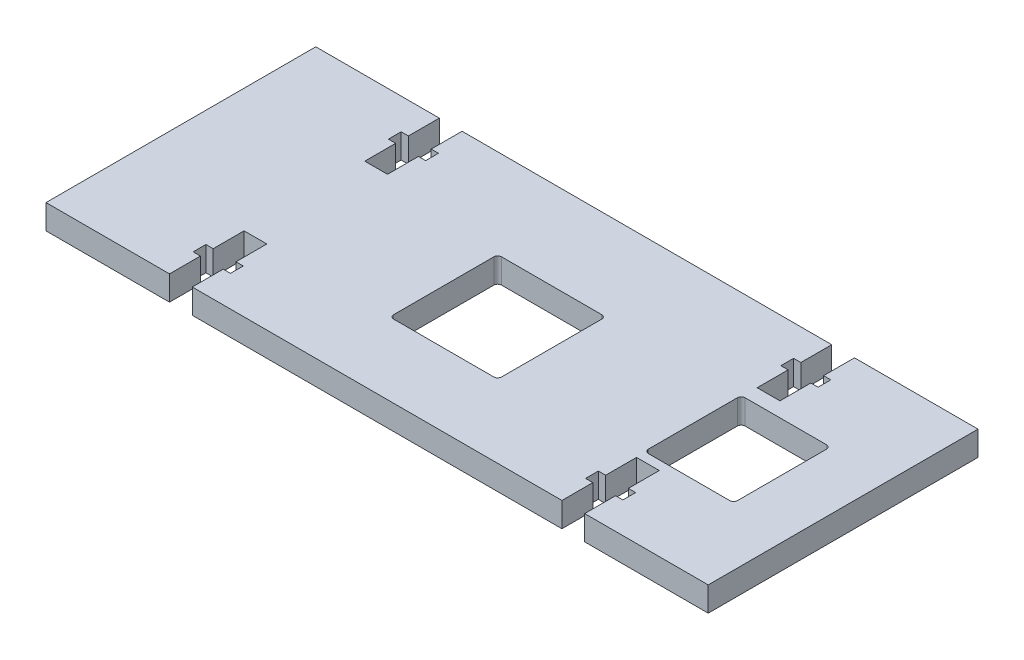
SolidWorks part; units mm, degrees
ref_plane "Front Plane" through (0, 0, 0) normal (0, 0, 1) x (1, 0, 0)
ref_plane "Top Plane" through (0, 0, 0) normal (0, 1, 0) x (1, 0, 0)
ref_plane "Right Plane" through (0, 0, 0) normal (1, 0, 0) x (0, 0, -1)
sketch "Sketch1" plane through (0, 0, 0) normal (0, 1, 0) x (1, 0, 0)
  line L1 (-42.8625, -17.4625) -> (42.8625, -17.4625)
  line L2 (-42.8625, -17.4625) -> (-42.8625, 17.4625)
  line L3 (-42.8625, 17.4625) -> (42.8625, 17.4625)
  line L4 (42.8625, -17.4625) -> (42.8625, 17.4625)
  line L5 (-42.8625, -17.4625) -> (42.8625, 17.4625) construction
  line L6 (-42.8625, 17.4625) -> (42.8625, -17.4625) construction
  point P0 (0, 0)
  dimension "D1" = 85.725
  dimension "D2" = 34.925
extrude "Boss-Extrude1" add sketch "Sketch1" along normal blind 3.175
sketch "Sketch2" plane through (0, 0, 0) normal (0, -1, 0) x (-1, 0, 0)
  line L0 (3.3881, -2.4141) -> (-1.7731, 0.3271) construction
  line L2 (7.7925, 5.9415) -> (-6.1775, 5.9415)
  line L3 (7.7925, 5.9415) -> (7.7925, -8.0285)
  line L4 (7.7925, -8.0285) -> (-6.1775, -8.0285)
  line L5 (-6.1775, 5.9415) -> (-6.1775, -8.0285)
  line L6 (7.7925, 5.9415) -> (-6.1775, -8.0285) construction
  line L7 (7.7925, -8.0285) -> (-6.1775, 5.9415) construction
  line L8 (-23.7675, -6.6175) -> (-35.3075, -6.6175)
  line L12 (-23.7675, 5.9065) -> (-23.7675, -6.6175)
  line L13 (-35.3075, 5.9065) -> (-23.7675, 5.9065)
  line L14 (-35.3075, 5.9065) -> (-35.3075, -6.6175)
  point P4 (0.8075, -1.0435)
  dimension "D1" = 13.97
  dimension "D2" = 13.97
extrude "Cut-Extrude1" cut sketch "Sketch2" against normal through all
fillet "Fillet1" radius 0.508 8 edges at (6.1775, 1.5875, -5.9415) (-7.7925, 1.5875, -5.9415) (6.1775, 1.5875, 8.0285) (-7.7925, 1.5875, 8.0285) (35.3075, 1.5875, -5.9065) (23.7675, 1.5875, -5.9065) (35.3075, 1.5875, 6.6175) (23.7675, 1.5875, 6.6175)
sketch "Sketch3" plane through (0, 0, 0) normal (0, -1, 0) x (1, 0, 0)
  line L0 (-42.8625, 17.4625) -> (42.8625, 17.4625) construction
  line L1 (-26.8732, 17.4625) -> (-23.9268, 17.4625)
  line L2 (-26.8732, 17.4625) -> (-26.8732, 13.462)
  line L3 (-26.8732, 7.8105) -> (-23.9268, 7.8105)
  line L4 (-23.9268, 17.4625) -> (-23.9268, 13.462)
  line L5 (-26.8732, 17.4625) -> (-23.9268, 7.8105) construction
  line L6 (-26.8732, 13.462) -> (-27.813, 13.462)
  line L7 (-22.987, 11.811) -> (-23.9268, 11.811)
  line L8 (-22.987, 11.811) -> (-22.987, 13.462)
  line L9 (-22.987, 13.462) -> (-23.9268, 13.462)
  line L10 (-27.813, 11.811) -> (-27.813, 13.462)
  line L11 (-22.987, 11.811) -> (-27.813, 13.462) construction
  line L12 (-22.987, 13.462) -> (-27.813, 11.811) construction
  line L13 (-23.9268, 11.811) -> (-23.9268, 7.8105)
  line L14 (-26.8732, 11.811) -> (-27.813, 11.811)
  line L15 (-26.8732, 11.811) -> (-26.8732, 7.8105)
  line L16 (-25.4, 7.8105) -> (-25.4, 17.4625) construction
  line L17 (0, 17.4625) -> (0, -17.4625) construction
  line L18 (42.8625, -17.4625) -> (-42.8625, -17.4625) construction
  line L19 (25.4, 7.8105) -> (25.4, 17.4625) construction
  line L20 (22.987, 13.462) -> (27.813, 11.811) construction
  line L21 (22.987, 11.811) -> (27.813, 13.462) construction
  line L22 (26.8732, 17.4625) -> (23.9268, 7.8105) construction
  line L23 (26.8732, 11.811) -> (26.8732, 7.8105)
  line L24 (26.8732, 11.811) -> (27.813, 11.811)
  line L25 (23.9268, 11.811) -> (23.9268, 7.8105)
  line L26 (27.813, 11.811) -> (27.813, 13.462)
  line L27 (22.987, 13.462) -> (23.9268, 13.462)
  line L28 (22.987, 11.811) -> (22.987, 13.462)
  line L29 (22.987, 11.811) -> (23.9268, 11.811)
  line L30 (26.8732, 13.462) -> (27.813, 13.462)
  line L31 (23.9268, 17.4625) -> (23.9268, 13.462)
  line L32 (26.8732, 7.8105) -> (23.9268, 7.8105)
  line L33 (26.8732, 17.4625) -> (26.8732, 13.462)
  line L34 (26.8732, 17.4625) -> (23.9268, 17.4625)
  line L35 (-42.8625, 0) -> (-37.7203, 0) construction
  line L36 (-42.8625, -17.4625) -> (-42.8625, 17.4625) construction
  line L37 (26.8732, -17.4625) -> (23.9268, -7.8105) construction
  line L38 (22.987, -11.811) -> (27.813, -13.462) construction
  line L39 (22.987, -13.462) -> (27.813, -11.811) construction
  line L40 (25.4, -7.8105) -> (25.4, -17.4625) construction
  line L41 (26.8732, -17.4625) -> (23.9268, -17.4625)
  line L42 (26.8732, -17.4625) -> (26.8732, -13.462)
  line L43 (26.8732, -7.8105) -> (23.9268, -7.8105)
  line L44 (23.9268, -17.4625) -> (23.9268, -13.462)
  line L45 (26.8732, -13.462) -> (27.813, -13.462)
  line L46 (22.987, -11.811) -> (23.9268, -11.811)
  line L47 (22.987, -11.811) -> (22.987, -13.462)
  line L48 (22.987, -13.462) -> (23.9268, -13.462)
  line L49 (27.813, -11.811) -> (27.813, -13.462)
  line L50 (23.9268, -11.811) -> (23.9268, -7.8105)
  line L51 (26.8732, -11.811) -> (27.813, -11.811)
  line L52 (26.8732, -11.811) -> (26.8732, -7.8105)
  line L53 (-25.4, -7.8105) -> (-25.4, -17.4625) construction
  line L54 (-22.987, -13.462) -> (-27.813, -11.811) construction
  line L55 (-22.987, -11.811) -> (-27.813, -13.462) construction
  line L56 (-26.8732, -17.4625) -> (-23.9268, -7.8105) construction
  line L57 (-26.8732, -11.811) -> (-26.8732, -7.8105)
  line L58 (-26.8732, -11.811) -> (-27.813, -11.811)
  line L59 (-23.9268, -11.811) -> (-23.9268, -7.8105)
  line L60 (-27.813, -11.811) -> (-27.813, -13.462)
  line L61 (-22.987, -13.462) -> (-23.9268, -13.462)
  line L62 (-22.987, -11.811) -> (-22.987, -13.462)
  line L63 (-22.987, -11.811) -> (-23.9268, -11.811)
  line L64 (-26.8732, -13.462) -> (-27.813, -13.462)
  line L65 (-23.9268, -17.4625) -> (-23.9268, -13.462)
  line L66 (-26.8732, -7.8105) -> (-23.9268, -7.8105)
  line L67 (-26.8732, -17.4625) -> (-26.8732, -13.462)
  line L68 (-26.8732, -17.4625) -> (-23.9268, -17.4625)
  point P6 (-25.4, 12.6365)
  point P18 (-25.4, 12.6365)
  point P36 (25.4, 12.6365)
  point P56 (25.4, -12.6365)
  point P71 (-25.4, -12.6365)
  dimension "D1" = 9.652
  dimension "D2" = 2.9464
  dimension "D3" = 1.651
  dimension "D4" = 4.826
  dimension "D5" = 25.4
extrude "Cut-Extrude2" cut sketch "Sketch3" against normal through all
